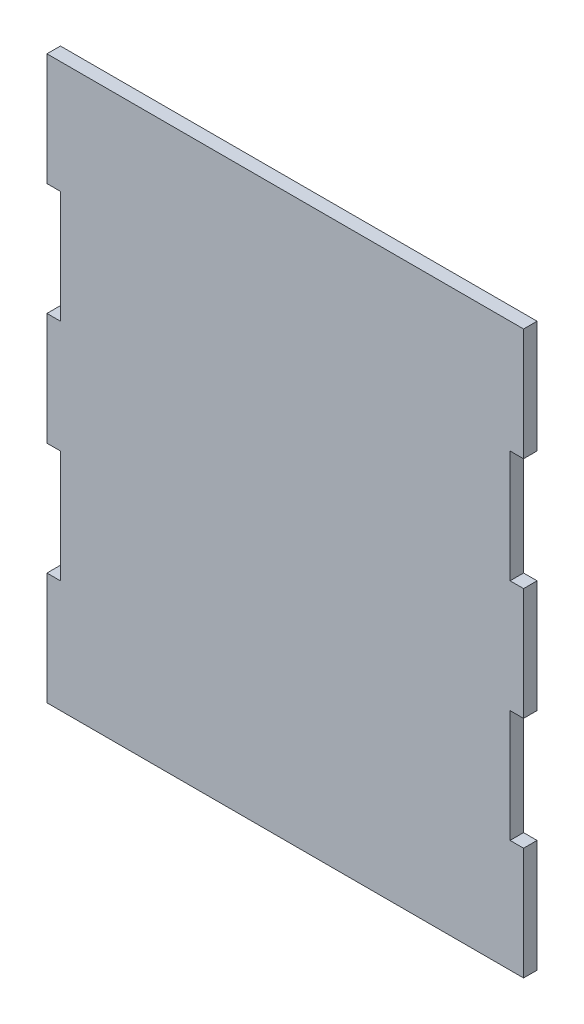
SolidWorks part; units mm, degrees
ref_plane "Front" through (0, 0, 0) normal (0, 0, 1) x (1, 0, 0)
ref_plane "Top" through (0, 0, 0) normal (0, 1, 0) x (1, 0, 0)
ref_plane "Right" through (0, 0, 0) normal (1, 0, 0) x (0, 0, -1)
sketch "Croquis1" plane through (0, 0, 0) normal (0, 0, 1) x (1, 0, 0)
  line L0 (-53, 0) -> (53, 0)
  line L1 (53, 0) -> (53, -25)
  line L2 (53, -25) -> (50, -25)
  line L3 (50, -25) -> (50, -50)
  line L4 (53, -50) -> (50, -50)
  line L5 (53, -50) -> (53, -75)
  line L6 (53, -75) -> (50, -75)
  line L7 (50, -75) -> (50, -100)
  line L8 (53, -100) -> (50, -100)
  line L9 (53, -100) -> (53, -125)
  line L10 (53, -125) -> (-53, -125)
  line L11 (0, 0) -> (0, -125) construction
  line L12 (-53, -100) -> (-53, -125)
  line L13 (-53, -100) -> (-50, -100)
  line L14 (-50, -75) -> (-50, -100)
  line L15 (-53, -75) -> (-50, -75)
  line L16 (-53, -50) -> (-53, -75)
  line L17 (-53, -50) -> (-50, -50)
  line L18 (-50, -25) -> (-50, -50)
  line L19 (-53, -25) -> (-50, -25)
  line L20 (-53, 0) -> (-53, -25)
  dimension "D1" = 53
  dimension "D2" = 25
  dimension "D3" = 25
  dimension "D4" = 3
  dimension "D7" = 25
  dimension "D9" = 25
  dimension "D6" = 2
extrude "Saliente-Extruir1" add sketch "Croquis1" along normal blind 3
